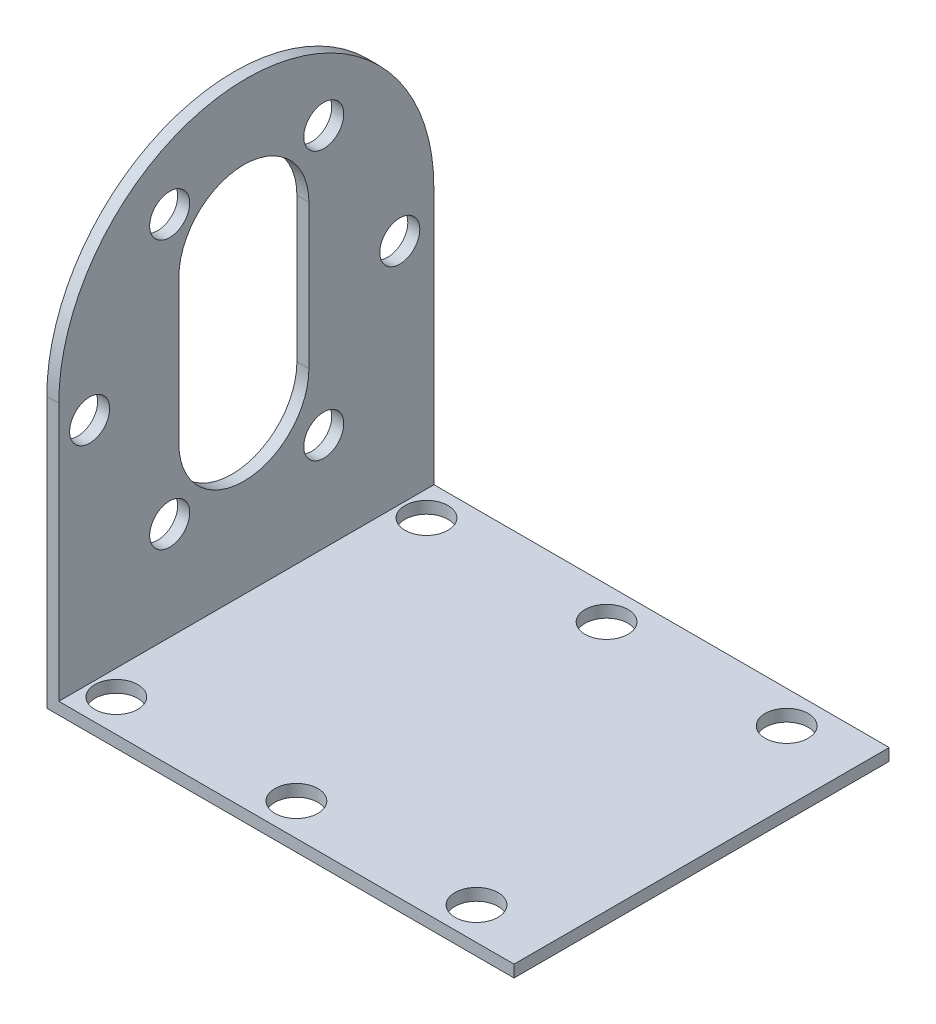
SolidWorks part; units mm, degrees
ref_plane "Plan de face" through (0, 0, 0) normal (0, 0, 1) x (1, 0, 0)
ref_plane "Plan de dessus" through (0, 0, 0) normal (0, 1, 0) x (1, 0, 0)
ref_plane "Plan de droite" through (0, 0, 0) normal (1, 0, 0) x (0, 0, -1)
sketch "Esquisse1" plane through (0, 0, 0) normal (0, 1, 0) x (1, 0, 0)
  line L1 (0, 0) -> (45.5, 0)
  line L2 (0, 0) -> (0, 37.5)
  line L3 (0, 37.5) -> (45.5, 37.5)
  line L4 (45.5, 0) -> (45.5, 37.5)
  circle A0 centre (2.5, 34.25) radius 2.15
  circle A1 centre (20.5, 34.25) radius 2.15
  circle A2 centre (38.5, 34.25) radius 2.15
  circle A3 centre (2.5, 3.25) radius 2.15
  circle A4 centre (20.5, 3.25) radius 2.15
  circle A5 centre (38.5, 3.25) radius 2.15
  dimension "D3" = 4.3
  dimension "D4" = 4.3
  dimension "D5" = 4.3
  dimension "D6" = 4.3
  dimension "D7" = 4.3
  dimension "D8" = 4.3
  dimension "D14" = 18
  dimension "D15" = 3.25
  dimension "D1" = 45.5
  dimension "D2" = 37.5
  dimension "D9" = 18
  dimension "D10" = 18
  dimension "D11" = 7
  dimension "D12" = 7
  dimension "D13" = 18
  dimension "D16" = 3.25
  dimension "D17" = 2.5
  dimension "D18" = 31
extrude "Boss.-Extru.1" add sketch "Esquisse1" along normal blind 1.2
ref_plane "Plan3" through (0, 0, 0) normal (-1, 0, 0) x (0, 0, 1)
sketch "Esquisse4" plane through (0, 0, 0) normal (-1, 0, 0) x (0, 0, 1)
  line L0 (-37.4819, 0) -> (-37.4819, 27)
  line L1 (0, 0) -> (0, 27)
  line L2 (-37.4819, 0) -> (0, 0)
  arc A0 (0, 27) -> (-37.4819, 27) centre (-18.7409, 27) ccw
  dimension "D1" = 27
  dimension "D2" = 27
extrude "Boss.-Extru.2" add sketch "Esquisse4" along normal blind 1.2
sketch "Esquisse5" plane through (0, 0, 0) normal (1, 0, 0) x (0, 0, -1)
  line L0 (18.5, 31.9) -> (18.5, 17.5) construction
  line L1 (25, 31.9) -> (25, 17.5)
  line L2 (12, 31.9) -> (12, 17.5)
  line L3 (18.5, 38.4) -> (-42.4539, 38.4) construction
  line L4 (18.5, 11) -> (-44.1288, 11) construction
  line L5 (0, 1.2) -> (0, 27) construction
  arc A0 (25, 31.9) -> (12, 31.9) centre (18.5, 31.9) ccw
  arc A1 (12, 17.5) -> (25, 17.5) centre (18.5, 17.5) ccw
  point P2 (18.5, 24.7)
  dimension "D1" = 13
  dimension "D2" = 27.4
  dimension "D3" = 12
  dimension "D4" = 11
extrude "Enlèv. mat.-Extru.2" cut sketch "Esquisse5" against normal through all
sketch "Esquisse9" plane through (0, 0, 0) normal (1, 0, 0) x (0, 0, -1)
  line L0 (26.4819, 9) -> (65.5084, 9) construction
  line L1 (28.4819, 11) -> (28.4819, 54.8289) construction
  line L2 (37.4819, 27) -> (37.4819, 1.2) construction
  line L3 (26.4819, 35.8) -> (72.8436, 35.8) construction
  line L4 (26.4819, 13) -> (71.3918, 13) construction
  line L5 (13.0819, 11) -> (13.0819, 61.6259) construction
  line L6 (24.4819, 11) -> (24.4819, 61.6259) construction
  line L7 (36.0819, 24) -> (36.0819, 44.5879) construction
  line L8 (34.0819, 22) -> (81.7159, 22) construction
  line L9 (5.0819, 24) -> (5.0819, 53.532) construction
  line L10 (32.0819, 24) -> (32.0819, 56.2368) construction
  circle A0 centre (26.4819, 11) radius 2
  circle A1 centre (26.4819, 37.8) radius 2
  circle A2 centre (11.0819, 11) radius 2
  circle A3 centre (11.0819, 37.8) radius 2
  circle A4 centre (34.0819, 24) radius 2
  circle A5 centre (3.0819, 24) radius 2
  dimension "D1" = 4
  dimension "D4" = 4
  dimension "D7" = 4
  dimension "D10" = 4
  dimension "D2" = 9
  dimension "D3" = 9
  dimension "D5" = 22.8
  dimension "D6" = 11.4
  dimension "D8" = 22
  dimension "D9" = 1.4
  dimension "D11" = 27
extrude "Enlèv. mat.-Extru.3" cut sketch "Esquisse9" against normal through all
sketch "Esquisse11" plane through (0, 0, 0) normal (0, -1, 0) x (-1, 0, 0)
  line L0 (-0.35, 3.25) -> (-0.35, -19.6146) construction
  line L2 (1.2, 37.4819) -> (1.2, 0) construction
  circle A0 centre (-2.5, 3.25) radius 2.15 construction
  dimension "D1" = 1.55
sketch "Esquisse12" plane through (0, 0, 0) normal (0, -1, 0) x (1, 0, 0)
sketch "Sketch1" plane through (0, 1.2, 0) normal (0, 1, 0) x (1, 0, 0)
  circle A0 centre (2.5, 3.25) radius 2.15 construction
  circle A2 centre (2.5, 3.25) radius 2.15
  circle A3 centre (20.5, 3.25) radius 2.15 construction
  circle A4 centre (20.5, 3.25) radius 2.15
